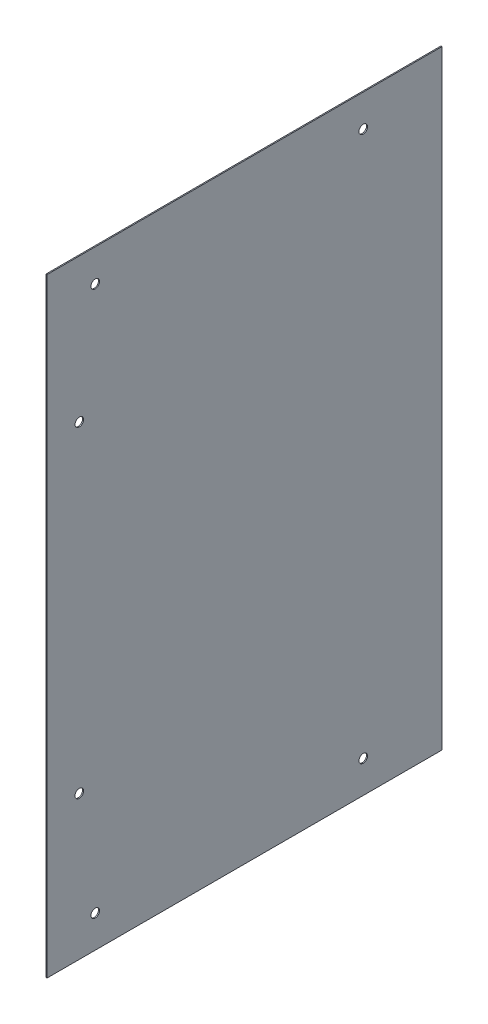
SolidWorks part; units mm, degrees
ref_plane "Front Plane" through (0, 0, 0) normal (1, 0, 0) x (0, 1, 0)
ref_plane "Top Plane" through (0, 0, 0) normal (0, 0, 1) x (0, 1, 0)
ref_plane "Right Plane" through (0, 0, 0) normal (0, 1, 0) x (-1, 0, 0)
sketch "Sketch1" plane through (0, 0, 0) normal (1, 0, 0) x (0, 1, 0)
  line L0 (-284.125, 184.125) -> (284.125, 184.125)
  line L1 (-300, -200) -> (300, -200) construction
  line L2 (-300, -200) -> (-300, 200) construction
  line L3 (-300, 200) -> (300, 200) construction
  line L4 (300, -200) -> (300, 200) construction
  line L5 (-300, -200) -> (300, 200) construction
  line L6 (-300, 200) -> (300, -200) construction
  line L7 (284.125, -184.125) -> (284.125, 184.125)
  line L8 (-284.125, -184.125) -> (284.125, -184.125)
  line L9 (-284.125, -184.125) -> (-284.125, 184.125)
  point P0 (0, 0)
  dimension "D1" = 600
  dimension "D2" = 400
  dimension "D3" = 15.875
extrude "Boss-Extrude1" add sketch "Sketch1" along normal mid plane 1
sketch "Sketch2" plane through (0.5, 0, 0) normal (1, 0, 0) x (0, 0, -1)
  line L0 (-184.125, -284.125) -> (-184.125, 284.125) construction
  line L1 (-184.125, -284.125) -> (-184.125, 284.125)
  line L2 (-184.125, -150) -> (-184.125, 150) construction
  line L3 (-184.125, 150) -> (-154.125, 150) construction
  line L4 (-184.125, -150) -> (-154.125, -150) construction
  line L6 (-139.2611, -284.125) -> (110.7389, -284.125) construction
  line L8 (184.125, -284.125) -> (-184.125, -284.125) construction
  line L9 (-139.2611, -284.125) -> (-139.2611, -254.125) construction
  line L10 (110.7389, -284.125) -> (110.7389, -254.125) construction
  line L11 (-184.125, 0) -> (184.125, 0) construction
  line L12 (184.125, -284.125) -> (184.125, 284.125) construction
  circle A1 centre (-154.125, 150) radius 4
  circle A2 centre (-154.125, -150) radius 4
  circle A3 centre (-139.2611, -254.125) radius 4
  circle A4 centre (110.7389, -254.125) radius 4
  circle A5 centre (110.7389, 254.125) radius 4
  circle A6 centre (-139.2611, 254.125) radius 4
  point P5 (-184.125, 0)
  point P14 (-14.2611, -284.125)
  dimension "D2" = 8
  dimension "D3" = 300
  dimension "D5" = 8
  dimension "D1" = 30
  dimension "D4" = 250
  dimension "D6" = 30
extrude "Cut-Extrude1" cut sketch "Sketch2" against normal through all both and the other way through all contours A2 | A1 | A6 | A5 | A3 | A4
